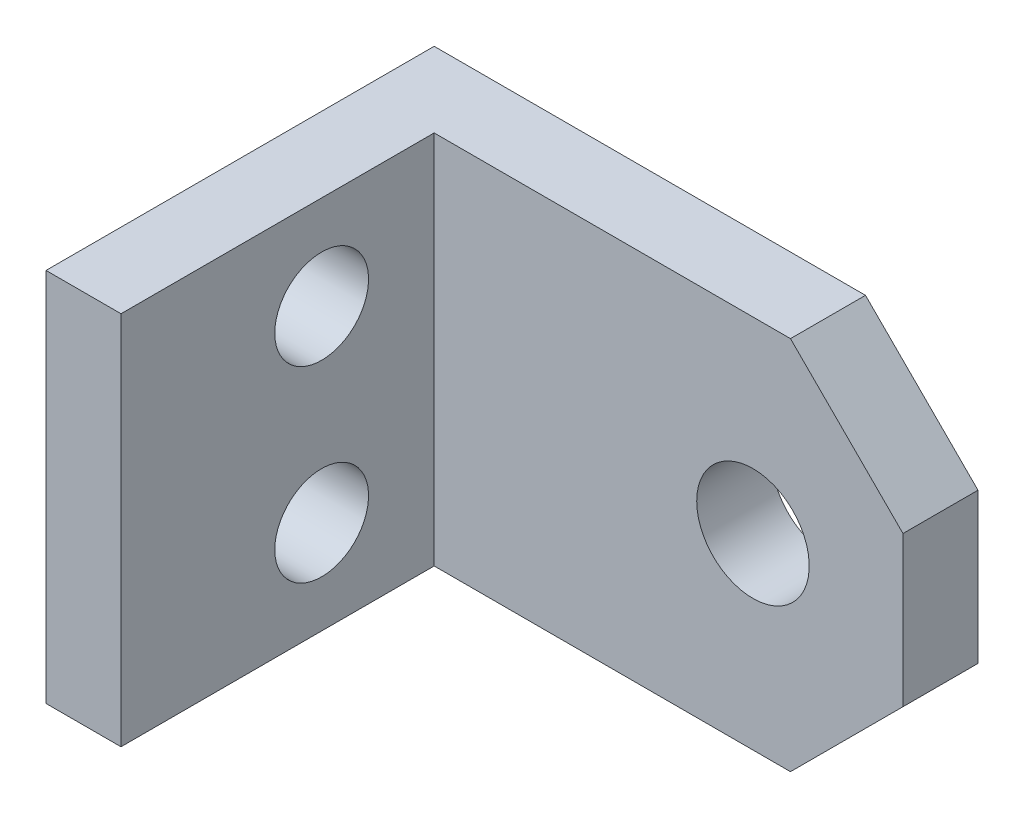
SolidWorks part; units mm, degrees
ref_plane "Спереди" through (0, 0, 0) normal (0, 0, 1) x (1, 0, 0)
ref_plane "Сверху" through (0, 0, 0) normal (0, 1, 0) x (1, 0, 0)
ref_plane "Справа" through (0, 0, 0) normal (1, 0, 0) x (0, 0, -1)
sketch "Эскиз1" plane through (0, 0, 0) normal (1, 0, 0) x (0, 0, -1)
  line L1 (0, 0) -> (20.7, 0)
  line L2 (0, 0) -> (0, 20)
  line L3 (0, 20) -> (20.7, 20)
  line L4 (20.7, 0) -> (20.7, 20)
  dimension "D1" = 20
  dimension "D2" = 20.7
extrude "Бобышка-Вытянуть1" add sketch "Эскиз1" along normal blind 4
sketch "Эскиз2" plane through (4, 0, 0) normal (1, 0, 0) x (0, 0, -1)
  line L0 (0, 0) -> (20.7, 0) construction
  line L1 (20.7, 20) -> (16.7, 20)
  line L2 (20.7, 20) -> (20.7, 0)
  line L3 (20.7, 0) -> (16.7, 0)
  line L4 (16.7, 20) -> (16.7, 0)
  dimension "D1" = 4
extrude "Бобышка-Вытянуть2" add sketch "Эскиз2" along normal blind 25
sketch "Эскиз3" plane through (0, 0, 0) normal (-1, 0, 0) x (0, 0, 1)
  line L0 (-10.7, 20) -> (-10.7, 0) construction
  line L1 (-20.7, 20) -> (0, 20) construction
  line L2 (0, 0) -> (-20.7, 0) construction
  line L3 (-20.7, 0) -> (-20.7, 20) construction
  circle A0 centre (-10.7, 15) radius 2.5
  circle A1 centre (-10.7, 5) radius 2.5
  dimension "D2" = 5
  dimension "D4" = 5
  dimension "D1" = 10
  dimension "D3" = 5
extrude "Вырез-Вытянуть1" cut sketch "Эскиз3" against normal blind 4
sketch "Эскиз4" plane through (0, 0, -20.7) normal (0, 0, -1) x (-1, 0, 0)
  line L0 (-29, 10) -> (0, 10) construction
  line L1 (-29, 0) -> (-29, 20) construction
  line L2 (0, 0) -> (0, 20) construction
  circle A0 centre (-21, 10) radius 3
  dimension "D1" = 6
  dimension "D2" = 21
extrude "Вырез-Вытянуть2" cut sketch "Эскиз4" against normal blind 4
chamfer "Фаска1" distance 6 angle 45 2 edges at (29, 0, -18.7) (29, 20, -18.7)
